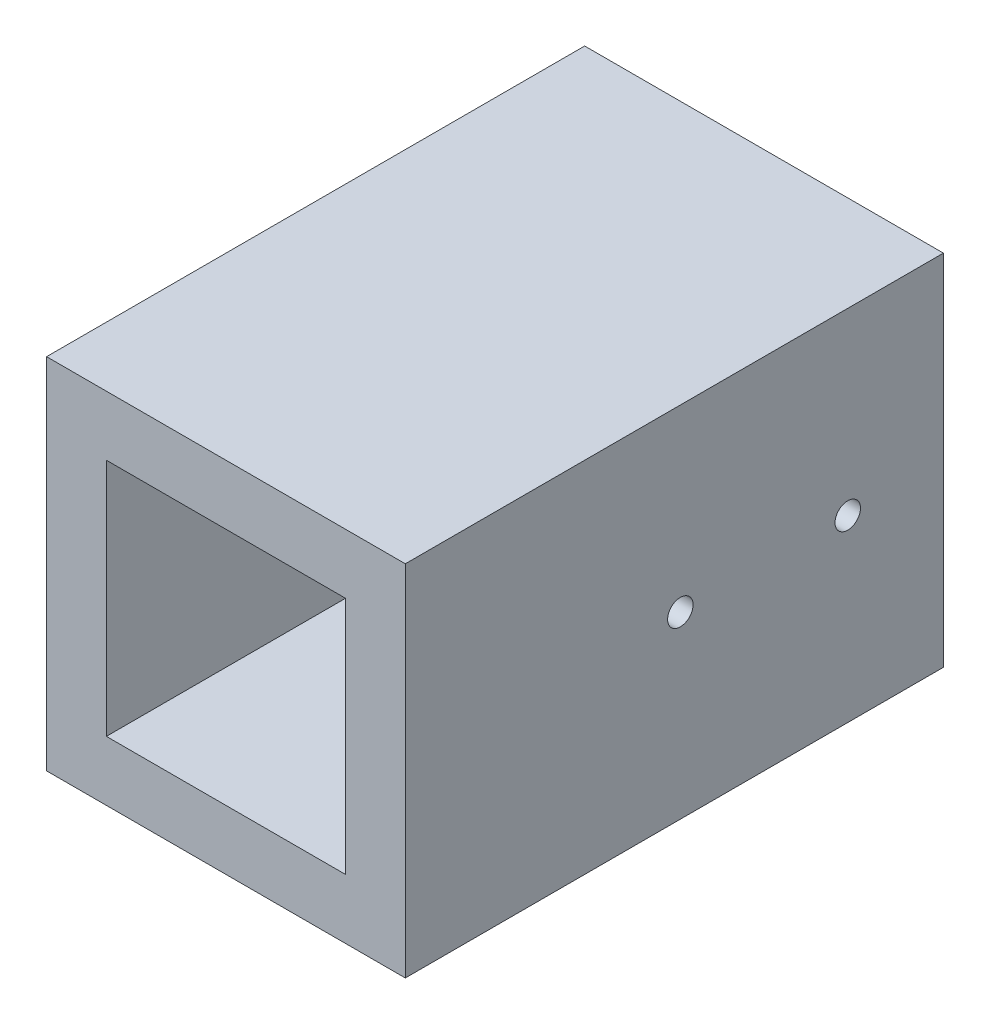
SolidWorks part; units mm, degrees
ref_plane "Front Plane" through (0, 0, 0) normal (0, 0, 1) x (1, 0, 0)
ref_plane "Top Plane" through (0, 0, 0) normal (0, 1, 0) x (1, 0, 0)
ref_plane "Right Plane" through (0, 0, 0) normal (1, 0, 0) x (0, 0, -1)
sketch "Sketch1" plane through (0, 0, 0) normal (0, 0, 1) x (1, 0, 0)
  line L0 (-12.7, 12.7) -> (12.7, 12.7)
  line L2 (-19.05, 19.05) -> (19.05, 19.05)
  line L3 (-19.05, 19.05) -> (-19.05, -19.05)
  line L4 (-19.05, -19.05) -> (19.05, -19.05)
  line L5 (19.05, 19.05) -> (19.05, -19.05)
  line L10 (12.7, 12.7) -> (12.7, -12.7)
  line L11 (-12.7, -12.7) -> (12.7, -12.7)
  line L12 (-12.7, 12.7) -> (-12.7, -12.7)
  point P12 (0, 19.05)
  point P14 (19.05, 0)
  dimension "Wall Thickness" = 6.35
  dimension "Outside Width" = 38.1
  dimension "Outside Height" = 38.1
  dimension "Inside Height" = 25.4
  dimension "Inside Width" = 25.4
sketch "Sketch2" plane through (0, 0, 0) normal (1, 0, 0) x (0, 0, -1)
  line L0 (76.2, 0) -> (-76.2, 0)
  point P4 (0, 0)
  point P7 (-76.2, 0)
  point P10 (76.2, 0)
  dimension "Length" = 152.4
sketch "Sketch3" plane through (0, 0, 0) normal (0, 0, 1) x (1, 0, 0)
  line L21 (19.05, 19.05) -> (-19.05, 19.05)
  line L22 (19.05, -19.05) -> (19.05, 19.05)
  line L23 (-19.05, -19.05) -> (19.05, -19.05)
  line L24 (-19.05, 19.05) -> (-19.05, -19.05)
  line L25 (19.05, 19.05) -> (-19.05, 19.05)
  line L26 (19.05, -19.05) -> (19.05, 19.05)
  line L27 (-19.05, -19.05) -> (19.05, -19.05)
  line L28 (-19.05, 19.05) -> (-19.05, -19.05)
  line L29 (12.7, 12.7) -> (-12.7, 12.7)
  line L30 (12.7, -12.7) -> (12.7, 12.7)
  line L31 (-12.7, -12.7) -> (12.7, -12.7)
  line L32 (-12.7, 12.7) -> (-12.7, -12.7)
  line L33 (12.7, 12.7) -> (-12.7, 12.7)
  line L34 (12.7, -12.7) -> (12.7, 12.7)
  line L35 (-12.7, -12.7) -> (12.7, -12.7)
  line L36 (-12.7, 12.7) -> (-12.7, -12.7)
  dimension "D1" = 0
  dimension "D2" = 0
extrude "Boss-Extrude1" add sketch "Sketch3" along normal up to vertex (76.2 mm away) and the other way up to vertex (76.2 mm away) up to point (0, 0, 76.2) other way up to point (0, 0, -76.2)
sketch "Drawing Reference" plane through (0, 0, 0) normal (1, 0, 0) x (0, 0, -1)
  line L0 (-76.2, 0) -> (76.2, 0) construction
  line L1 (0, -19.05) -> (0, 19.05) construction
  line L2 (-76.2, -19.05) -> (76.2, -19.05) construction
  line L5 (-76.2, 19.05) -> (76.2, 19.05) construction
  point P7 (-64.77, 0)
  point P8 (64.77, 0)
  dimension "D1" = 11.43
sketch "Sketch4" plane through (0, 0, -76.2) normal (0, 0, -1) x (-1, 0, 0)
  line L0 (-19.05, 19.05) -> (19.05, 19.05)
  line L1 (19.05, 19.05) -> (19.05, -19.05)
  line L2 (19.05, -19.05) -> (-19.05, -19.05)
  line L3 (-19.05, -19.05) -> (-19.05, 19.05)
  line L4 (-12.7, 12.7) -> (12.7, 12.7)
  line L5 (12.7, 12.7) -> (12.7, -12.7)
  line L6 (12.7, -12.7) -> (-12.7, -12.7)
  line L7 (-12.7, -12.7) -> (-12.7, 12.7)
extrude "Cut-Extrude1" cut sketch "Sketch4" against normal blind 95.25
sketch "Sketch7" plane through (-19.05, 0, 0) normal (-1, 0, 0) x (0, -1, 0)
  line L2 (19.05, 76.2) -> (19.05, 19.05) construction
  line L3 (19.05, 19.05) -> (-19.05, 19.05) construction
  circle A0 centre (0, 39.37) radius 3.81
  dimension "D3" = 7.62
  dimension "D1" = 19.05
  dimension "D2" = 20.32
extrude "Cut-Extrude4" cut sketch "Sketch7" against normal up to next
sketch "Sketch8" plane through (19.05, 0, 0) normal (1, 0, 0) x (0, 0, -1)
  line L0 (-19.05, 19.05) -> (-19.05, -19.05) construction
  line L1 (-76.2, -19.05) -> (-19.05, -19.05) construction
  point P0 (-29.21, 0)
  point P2 (-46.99, 0)
  dimension "D1" = 10.16
  dimension "D2" = 27.94
  dimension "D3" = 19.05
  dimension "D4" = 19.05
hole_wizard "#6-32 Tapped Hole1" positions "Sketch8" profile "Sketch9" tap size "#6-32" standard "ANSI Inch"
sketch "Sketch9" plane through (19.05, 0, 29.21) normal (0, 1, 0) x (0, 0, -1)
  line L0 (0, 0) -> (0, 6.35)
  line L1 (0, 6.35) -> (1.3525, 6.35)
  line L2 (1.3525, 6.35) -> (1.3525, 0)
  line L5 (1.3525, 0) -> (0, 0)
  line L11 (0, -6.35) -> (0, 107.95) construction
  dimension "Thru Tap Drill Dia." = 2.7051
  dimension "Thru Tap Drill Depth" = 6.35
cosmetic thread "Hole Thread1" parameters "D2"=3.5052
cosmetic thread "Hole Thread2" parameters "D2"=3.5052
equation "\"D1@Drawing Reference\"=\"Outside Width@Sketch1\" * .3"
